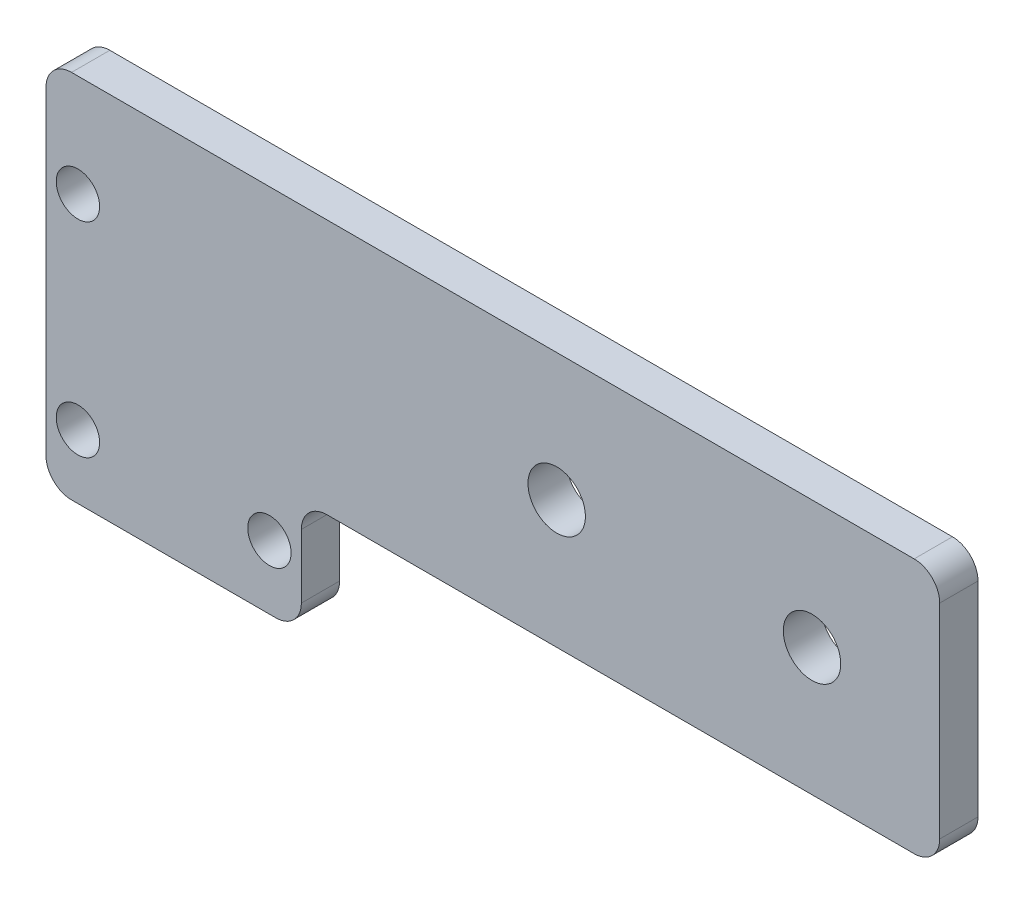
SolidWorks part; units mm, degrees
material "1023 Kohlenstoffstahlblech (SS)"
ref_plane "Ebene vorne" through (0, 0, 0) normal (0, 0, 1) x (1, 0, 0)
ref_plane "Ebene oben" through (0, 0, 0) normal (0, 1, 0) x (1, 0, 0)
ref_plane "Ebene rechts" through (0, 0, 0) normal (1, 0, 0) x (0, 0, -1)
sketch "Skizze1" plane through (0, 0, 0) normal (0, 0, 1) x (1, 0, 0)
  line L0 (0, 0) -> (0, -9)
  line L1 (0, -9) -> (-5, -9)
  line L2 (-5, -9) -> (-5, -21)
  line L3 (-15, -21) -> (-15, -9)
  line L4 (-15, -9) -> (-20, -9)
  line L5 (-20, -9) -> (-20, 20)
  line L6 (-20, 20) -> (50, 20)
  line L7 (50, 20) -> (50, 0)
  line L8 (50, 0) -> (0, 0)
  arc A0 (-15, -21) -> (-5, -21) centre (-10, -21) ccw
  dimension "D4" = 10
  dimension "D1" = 20
  dimension "D2" = 29
  dimension "D3" = 20
  dimension "D5" = 12
  dimension "D6" = 50
extrude "Aufsatz-Linear austragen1" add sketch "Skizze1" along normal blind 3
sketch "Skizze2" plane through (0, 0, 3) normal (0, 0, 1) x (1, 0, 0)
  arc A0 (-15, -21) -> (-5, -21) centre (-10, -21) ccw construction
  arc A1 (-15, -21) -> (-5, -21) centre (-10, -21) ccw construction
  circle A2 centre (-10, -21) radius 1.7
  dimension "D1" = 3.4
extrude "Schnitt-Linear austragen1" cut sketch "Skizze2" against normal through all
hole_wizard "Durchgangsloch für M41" positions "Skizze3" profile "Skizze5" hole size "M4" standard "ANSI Metrisch" end condition through all
sketch "Skizze3" plane through (0, 0, 3) normal (0, 0, 1) x (1, 0, 0)
  line L0 (50, 10) -> (40, 10) construction
  line L1 (50, 0) -> (50, 20) construction
  line L2 (40, 10) -> (20, 10) construction
  point P1 (40, 10)
  point P4 (20, 10)
  dimension "D1" = 10
  dimension "D2" = 20
sketch "Skizze5" plane through (20, 10, 3) normal (1, 0, 0) x (0, -1, 0)
  line L0 (0, 0) -> (0, 3)
  line L1 (0, 3) -> (2.25, 3)
  line L2 (2.25, 3) -> (2.25, 0)
  line L5 (2.25, 0) -> (0, 0)
  line L11 (0, -6.35) -> (0, 107.95) construction
  dimension "Bohrerdurchmesser" = 4.5
  dimension "Bohrungstiefe" = 3
hole_wizard "Durchgangsloch für M31" positions "Skizze7" profile "Skizze8" hole size "M3" standard "ANSI Metrisch" end condition through all
sketch "Skizze7" plane through (0, 0, 3) normal (0, 0, 1) x (1, 0, 0)
  line L1 (-17.5, 12) -> (-2.5, 12) construction
  line L2 (-17.5, 12) -> (-17.5, -4) construction
  line L3 (-17.5, -4) -> (-2.5, -4) construction
  line L4 (-2.5, 12) -> (-2.5, -4) construction
  line L5 (-10, -4) -> (-10, -26) construction
  arc A1 (-15, -21) -> (-5, -21) centre (-10, -21) ccw construction
  point P1 (-17.5, 12)
  point P2 (-2.5, -4)
  point P5 (-17.5, -4)
  dimension "D1" = 16
  dimension "D2" = 15
  dimension "D3" = 4
sketch "Skizze8" plane through (-17.5, 12, 3) normal (1, 0, 0) x (0, -1, 0)
  line L0 (0, 0) -> (0, 3)
  line L1 (0, 3) -> (1.7, 3)
  line L2 (1.7, 3) -> (1.7, 0)
  line L5 (1.7, 0) -> (0, 0)
  line L11 (0, -6.35) -> (0, 107.95) construction
  dimension "Bohrerdurchmesser" = 3.4
  dimension "Bohrungstiefe" = 3
fillet "Verrundung1" radius 2 8 edges at (-20, -9, 1.5) (-15, -9, 1.5) (-5, -9, 1.5) (0, -9, 1.5) (0, 0, 1.5) (50, 0, 1.5) (-20, 20, 1.5) (50, 20, 1.5)
sketch "Skizze9" plane through (0, 0, 3) normal (0, 0, 1) x (1, 0, 0)
  line L1 (-18, -9) -> (-2, -9)
  line L2 (-18, -9) -> (-18, -26)
  line L3 (-18, -26) -> (-2, -26)
  line L4 (-2, -9) -> (-2, -26)
  arc A0 (-15, -21) -> (-5, -21) centre (-10, -21) ccw construction
extrude "Schnitt-Linear austragen2" cut sketch "Skizze9" against normal through all
